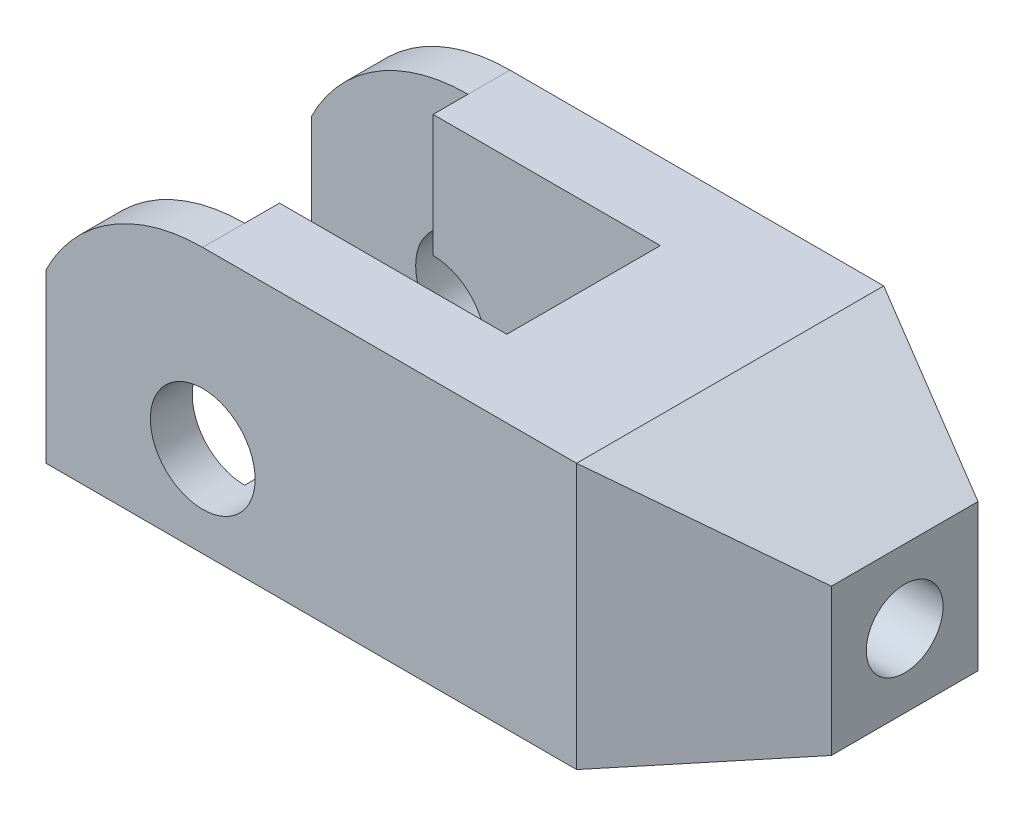
SolidWorks part; units mm, degrees
ref_plane "Front Plane" through (0, 0, 0) normal (0, 0, 1) x (1, 0, 0)
ref_plane "Top Plane" through (0, 0, 0) normal (0, 1, 0) x (1, 0, 0)
ref_plane "Right Plane" through (0, 0, 0) normal (1, 0, 0) x (0, 0, -1)
other "Configuration Table"
sketch "Sketch1" plane through (0, 0, 0) normal (0, 0, 1) x (1, 0, 0)
  line L1 (0, 0) -> (101, 0)
  line L2 (0, 0) -> (0, 38)
  line L3 (0, 38) -> (101, 38)
  line L4 (101, 0) -> (101, 38)
  dimension "D1" = 101
  dimension "D2" = 38
extrude "Boss-Extrude1" add sketch "Sketch1" along normal mid plane 44
sketch "Sketch2" plane through (0, 0, 0) normal (0, 0, 1) x (1, 0, 0)
  line L0 (76, 38) -> (101, 29.5)
  line L1 (101, 38) -> (0, 38) construction
  line L2 (101, 0) -> (101, 38) construction
  line L3 (101, 29.5) -> (101, 38)
  line L4 (101, 38) -> (76, 38)
  line L5 (101, 0) -> (76, 0)
  line L6 (0, 0) -> (101, 0) construction
  line L7 (76, 0) -> (101, 8.5)
  line L8 (101, 8.5) -> (101, 0)
  line L9 (0, 38) -> (0, 0) construction
  line L10 (22.4499, 38) -> (0, 38)
  line L11 (0, 38) -> (0, 24)
  circle A0 centre (22.4499, 13) radius 7.5
  arc A1 (22.4499, 38) -> (0, 24) centre (22.4499, 13) ccw
  dimension "D2" = 15
  dimension "D3" = 25
  dimension "D4" = 24
  dimension "D1" = 25
  dimension "D5" = 21
extrude "Cut-Extrude1" cut sketch "Sketch2" against normal through all both and the other way through all
sketch "Sketch3" plane through (0, 0, 0) normal (0, 1, 0) x (1, 0, 0)
  line L0 (76, 22) -> (101, 10.5)
  line L1 (101, 22) -> (101, -22) construction
  line L2 (101, 10.5) -> (101, 22)
  line L3 (101, 22) -> (76, 22)
  line L4 (-20.9, 0) -> (20.9, 0) construction
  line L5 (101, -22) -> (76, -22)
  line L6 (101, -10.5) -> (101, -22)
  line L7 (76, -22) -> (101, -10.5)
  line L8 (0, 16) -> (22.4499, 16)
  line L9 (0, 22) -> (0, -22) construction
  line L10 (22.4499, 16) -> (22.4499, 11)
  line L11 (22.4499, 11) -> (55, 11)
  line L12 (55, 11) -> (55, -11)
  line L13 (22.4499, -11) -> (55, -11)
  line L14 (22.4499, -16) -> (22.4499, -11)
  line L15 (0, -16) -> (22.4499, -16)
  line L16 (0, 16) -> (0, -16)
  line L17 (22.4499, 22) -> (22.4499, -22) construction
  point P20 (55, 0)
  dimension "D1" = 21
  dimension "D2" = 5
  dimension "D3" = 22
  dimension "D4" = 55
extrude "Cut-Extrude3" cut sketch "Sketch3" along normal up to next
sketch "Sketch4" plane through (101, 0, 0) normal (1, 0, 0) x (0, 0, -1)
  line L0 (10.5, 29.5) -> (10.5, 8.5) construction
  line L1 (10.5, 29.5) -> (-10.5, 29.5) construction
  circle A0 centre (0, 19) radius 5.5
  point P2 (0, 0)
  point P5 (10.5, 19)
  point P8 (0, 29.5)
  dimension "D1" = 11
extrude "Cut-Extrude4" cut sketch "Sketch4" against normal up to next
equation "\"GAUGE\"= SWITCH ( \"Thickness\" < 0.9 , 0 , \"Thickness\" < 1.1 , 20 , \"Thickness\" < 1.6 , 16 , \"Thickness\" < 2.1 , 14 , \"Thickness\" < 3.1 , 11 , \"Thickness\" < 4.8 , 7 , \"Thickness\" > 4.8 , 0 )"
